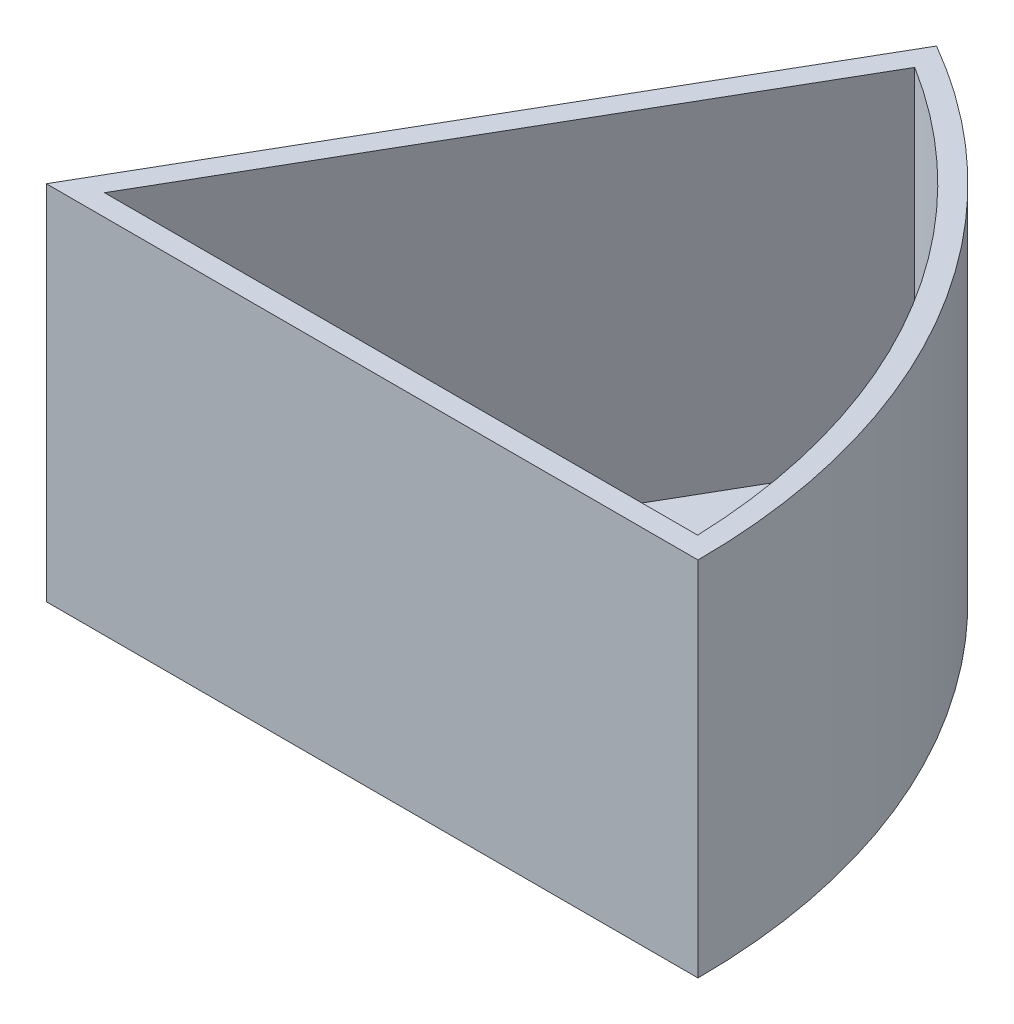
SolidWorks part; units mm, degrees
ref_plane "前视基准面" through (0, 0, 0) normal (0, 0, 1) x (1, 0, 0)
ref_plane "上视基准面" through (0, 0, 0) normal (0, 1, 0) x (1, 0, 0)
ref_plane "右视基准面" through (0, 0, 0) normal (1, 0, 0) x (0, 0, -1)
sketch "草图1" plane through (0, 0, 0) normal (0, 1, 0) x (1, 0, 0)
  line L0 (0, 0) -> (153, 0)
  line L1 (0, 0) -> (76.5, 132.5019)
  arc A0 (153, 0) -> (76.5, 132.5019) centre (0, 0) ccw
  dimension "D1" = 60
  dimension "D2" = 153
extrude "凸台-拉伸1" add sketch "草图1" along normal blind 5
sketch "草图2" plane through (0, 5, 0) normal (0, 1, 0) x (1, 0, 0)
  line L2 (76.5, 132.5019) -> (0, 0)
  line L3 (0, 0) -> (153, 0)
  line L4 (76.5, 132.5019) -> (0, 0)
  line L5 (0, 0) -> (153, 0)
  arc A1 (153, 0) -> (76.5, 132.5019) centre (0, 0) ccw
  arc A2 (153, 0) -> (76.5, 132.5019) centre (0, 0) ccw
  dimension "D1" = 0
extrude "拉伸-薄壁1" add sketch "草图2" along normal blind 80 thin thin type one direction reverse wall 5
